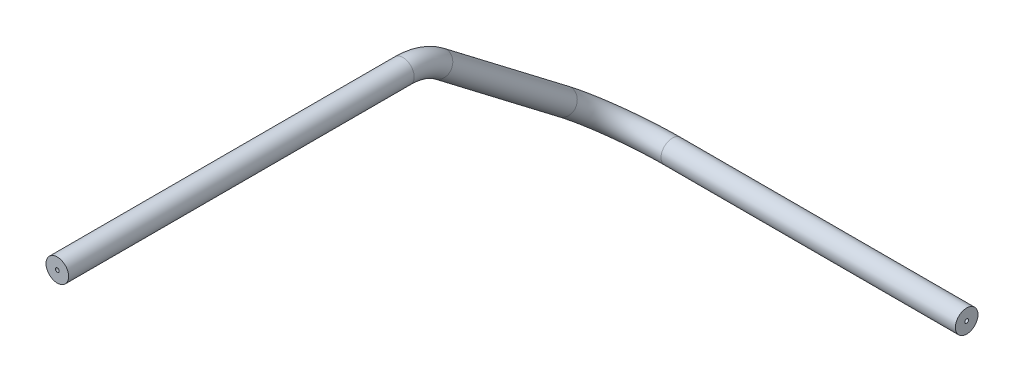
SolidWorks part; units mm, degrees
ref_plane "Front Plane" through (0, 0, 0) normal (0, 0, 1) x (1, 0, 0)
ref_plane "Top Plane" through (0, 0, 0) normal (0, 1, 0) x (1, 0, 0)
ref_plane "Right Plane" through (0, 0, 0) normal (1, 0, 0) x (0, 0, -1)
sketch "Skica1" plane through (0, 0, 0) normal (0, 0, 1) x (1, 0, 0)
  line L0 (0, 0) -> (94, 0)
  dimension "D1" = 94
sketch "Skica3" plane through (0, 0, 0) normal (1, 0, 0) x (0, 0, -1)
  line L0 (0, 0) -> (-50, 38.2)
  line L1 (-50, 38.2) -> (-147, 38.2)
  dimension "D1" = 147
  dimension "D2" = 50
  dimension "D3" = 38.2
ref_plane "Rovina1" through (94, 0, 0) normal (1, 0, 0) x (0, 0, -1)
sketch "Skica4" plane through (94, 0, 0) normal (1, 0, 0) x (0, 0, -1)
  circle A0 centre (0, 0) radius 3
  circle A1 centre (0, 0) radius 0.5
  dimension "D1" = 6
  dimension "D2" = 2.5
sketch3d "3DSkica1"
  line L0 (94, 0, 0) -> (16, 0, 0)
  line L1 (0, 9.7135, 12.7141) -> (0, 34.9141, 45.699)
  line L2 (0, 38.2, 55.4126) -> (0, 38.2, 147)
  arc A0 (0, 34.9141, 45.699) -> (0, 38.2, 55.4126) centre (0, 22.2, 55.4126) ccw
  arc A1 (16, 0, 0) -> (0, 9.7135, 12.7141) centre (16, 9.7135, 12.7141) ccw
  point P10 (0, 38.2, 50)
  point P11 (16, 22.2, 55.4126)
  point P14 (0, 0, 0)
  point P15 (16, 22.4276, 3.0005)
  dimension "D1" = 16
sweep "Táhnout po křivce1" add profiles "Skica4" path "3DSkica1"
